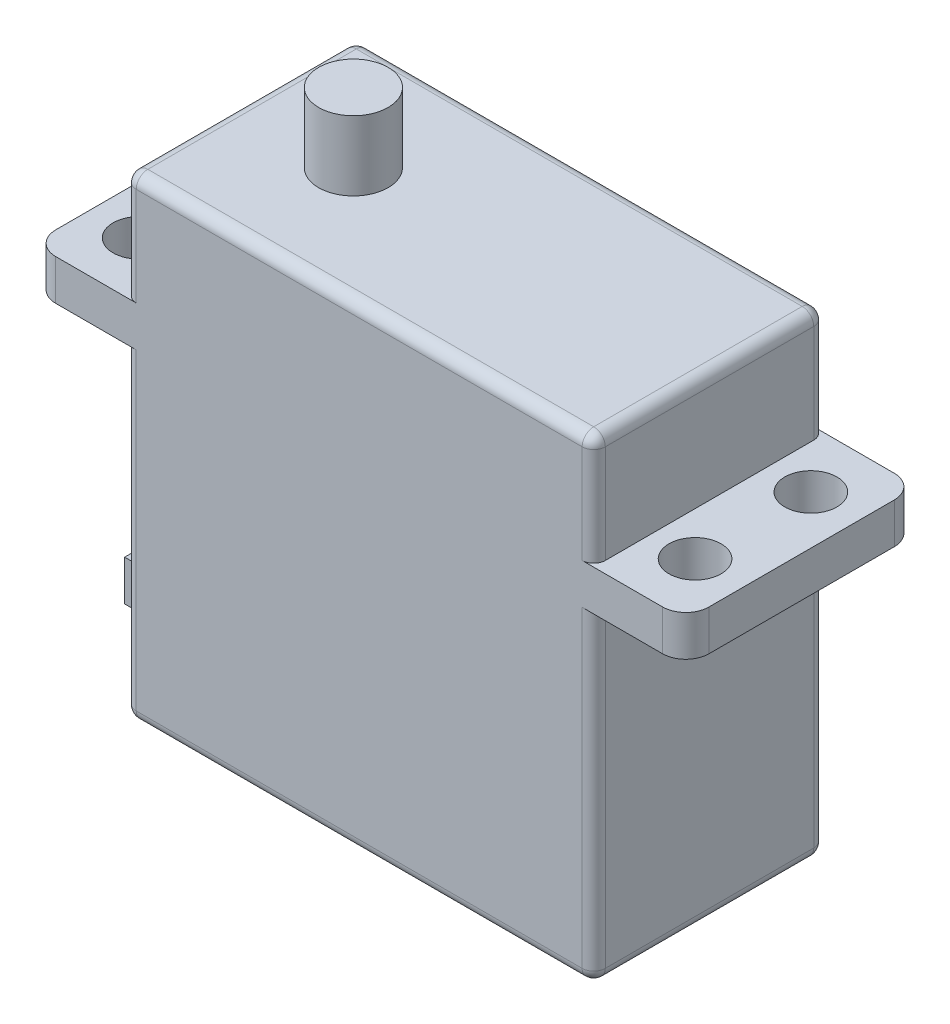
SolidWorks part; units mm, degrees
ref_plane "Front Plane" through (0, 0, 0) normal (0, 0, 1) x (1, 0, 0)
ref_plane "Top Plane" through (0, 0, 0) normal (0, 1, 0) x (1, 0, 0)
ref_plane "Right Plane" through (0, 0, 0) normal (1, 0, 0) x (0, 0, -1)
sketch "Sketch1" plane through (0, 0, 0) normal (0, 1, 0) x (1, 0, 0)
  line L1 (-20.25, 10) -> (20.25, 10)
  line L2 (-20.25, 10) -> (-20.25, -10)
  line L3 (-20.25, -10) -> (20.25, -10)
  line L4 (20.25, 10) -> (20.25, -10)
  line L5 (-20.25, 10) -> (20.25, -10) construction
  line L6 (-20.25, -10) -> (20.25, 10) construction
  point P0 (0, 0)
  dimension "D1" = 40.5
  dimension "D2" = 20
extrude "Boss-Extrude1" add sketch "Sketch1" along normal blind 41
ref_plane "Plane1" through (0, 28, 0) normal (0, -1, 0) x (-1, 0, 0)
sketch "Sketch2" plane through (0, 28, 0) normal (0, -1, 0) x (-1, 0, 0)
  line L1 (28.2, -10) -> (-28.2, -10)
  line L2 (28.2, -10) -> (28.2, 10)
  line L3 (28.2, 10) -> (-28.2, 10)
  line L4 (-28.2, -10) -> (-28.2, 10)
  line L5 (28.2, -10) -> (-28.2, 10) construction
  line L6 (28.2, 10) -> (-28.2, -10) construction
  line L7 (24, -5) -> (-24, -5) construction
  line L8 (24, -5) -> (24, 5) construction
  line L9 (24, 5) -> (-24, 5) construction
  line L10 (-24, -5) -> (-24, 5) construction
  line L11 (24, -5) -> (-24, 5) construction
  line L12 (24, 5) -> (-24, -5) construction
  circle A0 centre (-24, 5) radius 2.25
  circle A1 centre (24, 5) radius 2.25
  circle A2 centre (24, -5) radius 2.25
  circle A3 centre (-24, -5) radius 2.25
  point P0 (0, 0)
  point P6 (0, 0)
  dimension "D5" = 4.5
  dimension "D1" = 56.4
  dimension "D2" = 20
  dimension "D3" = 10
  dimension "D4" = 48
extrude "Boss-Extrude2" add sketch "Sketch2" against normal blind 3.5
sketch "Sketch3" plane through (0, 41, 0) normal (0, 1, 0) x (1, 0, 0)
  line L0 (-20.25, -10) -> (-20.25, 10) construction
  circle A0 centre (-10.5, 0) radius 3
  dimension "D3" = 6
  dimension "D1" = 0
  dimension "D2" = 9.75
extrude "Boss-Extrude3" add sketch "Sketch3" along normal blind 6
sketch "Sketch4" plane through (-20.25, 0, 0) normal (-1, 0, 0) x (0, 0, 1)
  line L0 (-10, 0) -> (10, 0) construction
  line L1 (5, 3.5) -> (-5, 3.5)
  line L2 (5, 3.5) -> (5, 7)
  line L3 (5, 7) -> (-5, 7)
  line L4 (-5, 3.5) -> (-5, 7)
  line L5 (5, 3.5) -> (-5, 7) construction
  line L6 (5, 7) -> (-5, 3.5) construction
  point P0 (0, 5.25)
  dimension "D1" = 10
  dimension "D2" = 3.5
  dimension "D3" = 0
  dimension "D4" = 3.5
extrude "Boss-Extrude4" add sketch "Sketch4" along normal blind 5
fillet "Fillet1" radius 2 4 edges at (28.2, 29.75, -10) (28.2, 29.75, 10) (-28.2, 29.75, -10) (-28.2, 29.75, 10)
fillet "Fillet2" radius 1 10 edges at (0, 0, -10) (-20.25, 0, 0) (0, 0, 10) (20.25, 0, 0) (20.25, 14, 10) (20.25, 14, -10) (-20.25, 36.25, -10) (-20.25, 14, -10) (-20.25, 14, 10) (-20.25, 36.25, 10)
fillet "Fillet3" radius 1 8 edges at (0.5, 41, 10) (-19.9571, 41, 9.7071) (-20.25, 41, 0) (-19.9571, 41, -9.7071) (20.25, 41, 0) (0.5, 41, -10) (20.25, 36.25, -10) (20.25, 36.25, 10)
ref_plane "Plane2" through (0, 22.25, 0) normal (0, -1, 0) x (-1, 0, 0)
